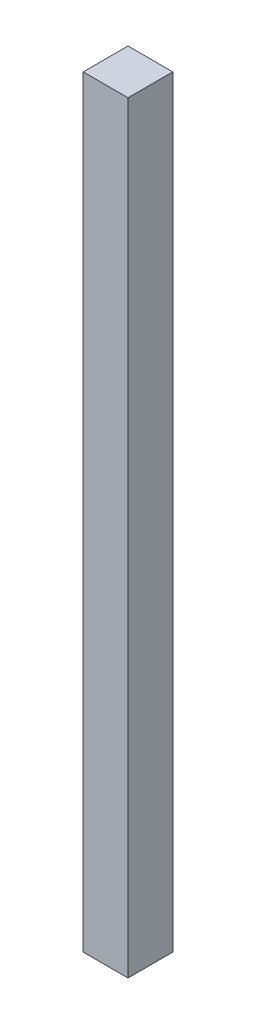
SolidWorks part; units mm, degrees
ref_plane "Front Plane" through (0, 0, 0) normal (0, 0, 1) x (1, 0, 0)
ref_plane "Top Plane" through (0, 0, 0) normal (0, 1, 0) x (1, 0, 0)
ref_plane "Right Plane" through (0, 0, 0) normal (1, 0, 0) x (0, 0, -1)
sketch "Sketch1" plane through (0, 0, 0) normal (0, 1, 0) x (1, 0, 0)
  line L1 (0, 0) -> (25.4, 0)
  line L2 (0, 0) -> (0, 25.4)
  line L3 (0, 25.4) -> (25.4, 25.4)
  line L4 (25.4, 0) -> (25.4, 25.4)
  dimension "D1" = 25.4
  dimension "D2" = 25.4
extrude "Boss-Extrude1" add sketch "Sketch1" along normal blind 431.8
